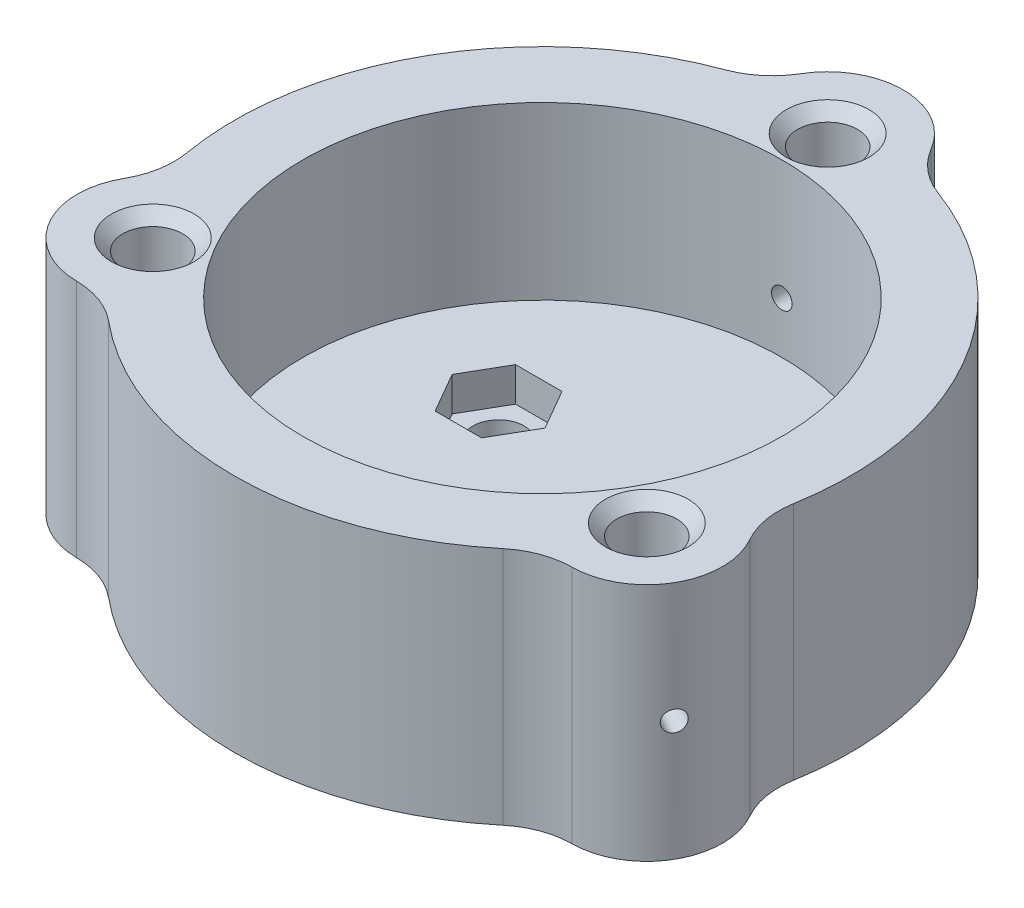
SolidWorks part; units mm, degrees
ref_plane "Спереди" through (0, 0, 0) normal (0, 0, 1) x (1, 0, 0)
ref_plane "Сверху" through (0, 0, 0) normal (0, 1, 0) x (1, 0, 0)
ref_plane "Справа" through (0, 0, 0) normal (1, 0, 0) x (0, 0, -1)
sketch "Эскиз1" plane through (0, 0, 0) normal (0, 1, 0) x (1, 0, 0)
  circle A0 centre (0, 0) radius 25 construction
  circle A1 centre (0, 25) radius 2.625
  circle A3 centre (0, 25) radius 6.625
  circle A4 centre (0, 0) radius 21
  circle A5 centre (0, 0) radius 27
  circle A6 centre (21.6506, -12.5) radius 6.625
  circle A7 centre (21.6506, -12.5) radius 2.625
  circle A8 centre (-21.6506, -12.5) radius 6.625
  circle A9 centre (-21.6506, -12.5) radius 2.625
  dimension "D1" = 50
  dimension "D2" = 5.25
  dimension "D3" = 4
  dimension "D5" = 4
  dimension "D4" = 2
  dimension "D6" = 3
extrude "Бобышка-Вытянуть1" add sketch "Эскиз1" along normal blind 15 contours A5 A3 A1 | A3 A5 A1 A4 | A6 A5 A3 A4 | A8 A4 A3 A5 | A7 A5 A6 A4 | A7 A5 A6 | A8 A5 A6 A4 | A9 A5 A8 | A9 A5 A8 A4
sketch "Эскиз2" plane through (0, 0, 0) normal (0, -1, 0) x (1, 0, 0)
  arc A27 (25.9493, 7.4589) -> (19.4343, 18.7433) centre (21.6506, 12.5) ccw
  arc A28 (6.515, -26.2022) -> (25.9493, 7.4589) centre (0, 0) ccw
  arc A29 (-6.515, -26.2022) -> (6.515, -26.2022) centre (0, -25) ccw
  arc A30 (-25.9493, 7.4589) -> (-6.515, -26.2022) centre (0, 0) ccw
  arc A31 (-19.4343, 18.7433) -> (-25.9493, 7.4589) centre (-21.6506, 12.5) ccw
  arc A32 (19.4343, 18.7433) -> (-19.4343, 18.7433) centre (0, 0) ccw
  arc A33 (25.9493, 7.4589) -> (19.4343, 18.7433) centre (21.6506, 12.5) ccw
  arc A34 (6.515, -26.2022) -> (25.9493, 7.4589) centre (0, 0) ccw
  arc A35 (-6.515, -26.2022) -> (6.515, -26.2022) centre (0, -25) ccw
  arc A36 (-25.9493, 7.4589) -> (-6.515, -26.2022) centre (0, 0) ccw
  arc A37 (-19.4343, 18.7433) -> (-25.9493, 7.4589) centre (-21.6506, 12.5) ccw
  arc A38 (19.4343, 18.7433) -> (-19.4343, 18.7433) centre (0, 0) ccw
  dimension "D1" = 0
extrude "Бобышка-Вытянуть2" add sketch "Эскиз2" along normal blind 6
fillet "Скругление1" radius 7 4 edges at (6.515, 4.5, -26.2022) (-19.4343, 4.5, 18.7433) (19.4343, 4.5, 18.7433) (25.9493, 4.5, 7.4589)
chamfer "Фаска1" distance 1 angle 45 3 edges at (0, 15, -22.375) (21.6506, 15, 15.125) (-21.6506, 15, 15.125)
sketch "Эскиз3" plane through (0, -6, 0) normal (0, -1, 0) x (1, 0, 0)
  circle A0 centre (0, 0) radius 10.5 construction
  circle A1 centre (0, 10.5) radius 2.25
  circle A2 centre (9.0933, -5.25) radius 2.25
  circle A3 centre (-9.0933, -5.25) radius 2.25
  dimension "D1" = 21
  dimension "D2" = 4.5
  dimension "D3" = 3
extrude "Вырез-Вытянуть1" cut sketch "Эскиз3" against normal through all
sketch "Эскиз4" plane through (0, 0, 0) normal (0, 1, 0) x (1, 0, 0)
  line L0 (-4.0703, -10.5) -> (-2.0352, -14.025)
  line L1 (11.1284, 1.725) -> (13.1636, 5.25)
  line L2 (13.1636, 5.25) -> (11.1284, 8.775)
  line L3 (11.1284, 8.775) -> (7.0581, 8.775)
  line L4 (7.0581, 8.775) -> (5.0229, 5.25)
  line L5 (5.0229, 5.25) -> (7.0581, 1.725)
  line L6 (7.0581, 1.725) -> (11.1284, 1.725)
  line L7 (-2.0352, -14.025) -> (2.0352, -14.025)
  line L8 (2.0352, -14.025) -> (4.0703, -10.5)
  line L9 (4.0703, -10.5) -> (2.0352, -6.975)
  line L10 (2.0352, -6.975) -> (-2.0352, -6.975)
  line L11 (-2.0352, -6.975) -> (-4.0703, -10.5)
  line L12 (-7.0581, 8.775) -> (-11.1284, 8.775)
  line L13 (-11.1284, 8.775) -> (-13.1636, 5.25)
  line L14 (-13.1636, 5.25) -> (-11.1284, 1.725)
  line L15 (-11.1284, 1.725) -> (-7.0581, 1.725)
  line L16 (-7.0581, 1.725) -> (-5.0229, 5.25)
  line L17 (-5.0229, 5.25) -> (-7.0581, 8.775)
  circle A0 centre (9.0933, 5.25) radius 3.525 construction
  circle A1 centre (0, -10.5) radius 3.525 construction
  circle A2 centre (-9.0933, 5.25) radius 3.525 construction
  circle A3 centre (0, -10.5) radius 2.25 construction
  dimension "D1" = 7.05
  dimension "D2" = 3
extrude "Вырез-Вытянуть2" cut sketch "Эскиз4" against normal blind 3
ref_plane "Плоскость1" through (0, 0, -31.625) normal (0, 0, -1) x (-1, 0, 0)
sketch "Эскиз5" plane through (0, 0, -31.625) normal (0, 0, -1) x (-1, 0, 0)
  line L0 (0, 15) -> (0, -6) construction
  line L1 (5.7106, 15) -> (-5.7106, 15) construction
  line L2 (-5.7106, -6) -> (5.7106, -6) construction
  circle A0 centre (0, 4.5) radius 0.9
  dimension "D1" = 1.8
extrude "Вырез-Вытянуть3" cut sketch "Эскиз5" against normal up to surface (10.6443 mm away)
pattern_circular "Круговой массив1" count 3 over 360 about axis through (0, 15, 0) along (0, -1, 0) of "Вырез-Вытянуть3"
equation "\"motor_diameter\"= 30"
equation "\"mm_diameter\"= IIF ( \"motor_diameter\" < 34 , 41 , \"motor_diameter\" + 8 )"
equation "\"upper_shafts_diameter\"= 5"
equation "\"upper_shats_length\"= 180"
equation "\"upper_bearing_d1\"= 10"
equation "\"upper_bearing_d2\"= 5"
equation "\"upper_bearing_h\"= 15"
equation "\"lower_shafts_diameter\"= 5"
equation "\"lower_shafts_length\"= 180"
equation "\"lower_bearing_d1\"= 10"
equation "\"lower_bearing_d2\"= 5"
equation "\"lower_bearing_h\"= 15"
equation "\"print_offset\"= 0.5"
equation "\"bh_screws_d\"= 2"
equation "\"bh_screws_h\"= 20"
equation "\"bh_screws_hh_d\"= 3.4"
equation "\"bh_screws_hh_h\"= 2"
equation "\"bh_nut_d\"= 3.8"
equation "\"bh_nut_h\"= 2"
equation "\"motor_screws_d\"= 3"
equation "\"motor_screws_h\"= 16"
equation "\"motor_screws_hh_d\"= 5.5"
equation "\"motor_screws_hh_h\"= 3"
equation "\"plate_hole_distance\"= 25.4"
equation "\"plate_screws_d\"= 6.5"
equation "\"shafts_diameter\"= IIF ( \"mm_diameter\" < 42 , 42 + 8 , \"mm_diameter\" + 8 )"
equation "\"central_hole_diameter\"= 8"
equation "\"bh_thikness\"= 4"
equation "\"D1@Эскиз1\"=\"shafts_diameter\""
equation "\"D2@Эскиз1\" = \"lower_shafts_diameter\" + \"print_offset\" / 2"
equation "\"D3@Эскиз1\"=\"bh_thikness\""
equation "\"D5@Эскиз1\"=\"D3@Эскиз1\""
equation "\"D1@Бобышка-Вытянуть1\"= \"lower_bearing_h\""
equation "\"D1@Бобышка-Вытянуть2\"=6"
equation "\"D4@Эскиз1\"=\"D3@Эскиз1\"/2"
equation "\"ends_screws_d\"= 4"
equation "\"ends_screws_h\"= 16"
equation "\"ends_screws_hh_d\"= 6.7"
equation "\"ends_screws_hh_h\"= 4.1"
equation "\"ends_nut_d\"= 6.8"
equation "\"ends_nut_h\"= 3"
equation "\"D2@Эскиз3\"=\"ends_screws_d\"+\"print_offset\""
equation "\"D1@Эскиз4\"=\"ends_nut_d\"+\"print_offset\"/2"
equation "\"D1@Вырез-Вытянуть2\"=\"ends_nut_h\""
equation "\"D1@Эскиз5\"=\"bh_screws_d\"-0.2"
